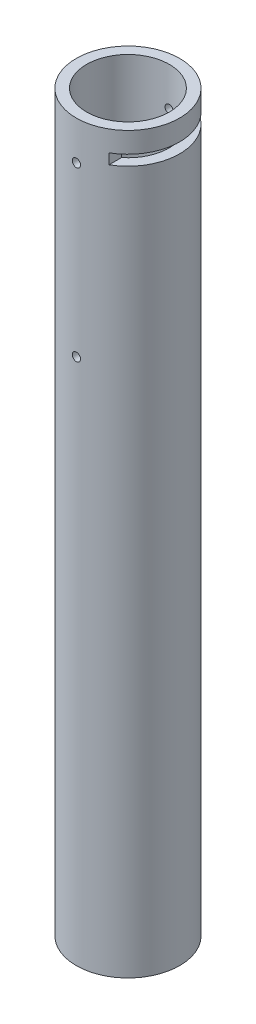
SolidWorks part; units mm, degrees
ref_plane "Front Plane" through (0, 0, 0) normal (0, 0, 1) x (1, 0, 0)
ref_plane "Top Plane" through (0, 0, 0) normal (0, 1, 0) x (1, 0, 0)
ref_plane "Right Plane" through (0, 0, 0) normal (1, 0, 0) x (0, 0, -1)
sketch "Sketch1" plane through (0, 0, 0) normal (0, 1, 0) x (1, 0, 0)
  circle A0 centre (0, 0) radius 31.75
  circle A1 centre (0, 0) radius 25.4
  dimension "D1" = 63.5
  dimension "D2" = 6.35
extrude "Boss-Extrude1" add sketch "Sketch1" along normal blind 450.85
sketch "Sketch4" plane through (0, 0, 0) normal (0, 0, 1) x (1, 0, 0)
  line L0 (31.75, 450.85) -> (31.75, 438.15)
  line L1 (31.75, 0) -> (31.75, 450.85) construction
  line L3 (31.75, 438.15) -> (15.875, 438.15)
  line L6 (15.875, 438.15) -> (15.875, 431.8)
  line L8 (15.875, 431.8) -> (31.75, 431.8)
  line L9 (31.75, 431.8) -> (31.75, 438.15)
  line L10 (0, 450.85) -> (0, 427.0375) construction
  line L11 (25.4, 450.85) -> (-25.4, 450.85) construction
  line L12 (0, 427.0375) -> (0, 323.85) construction
  line L13 (31.75, 450.85) -> (-31.75, 450.85) construction
  line L14 (15.875, 434.975) -> (31.75, 434.975) construction
  circle A2 centre (0, 427.0375) radius 2.54
  circle A3 centre (0, 323.85) radius 2.54
  dimension "D4" = 5.08
  dimension "D1" = 6.35
  dimension "D2" = 15.875
  dimension "D3" = 15.875
  dimension "D5" = 23.8125
  dimension "D6" = 127
extrude "Cut-Extrude2" cut sketch "Sketch4" against normal through all both and the other way through all contours A3 | A2 | L8 L9 L3 L6
